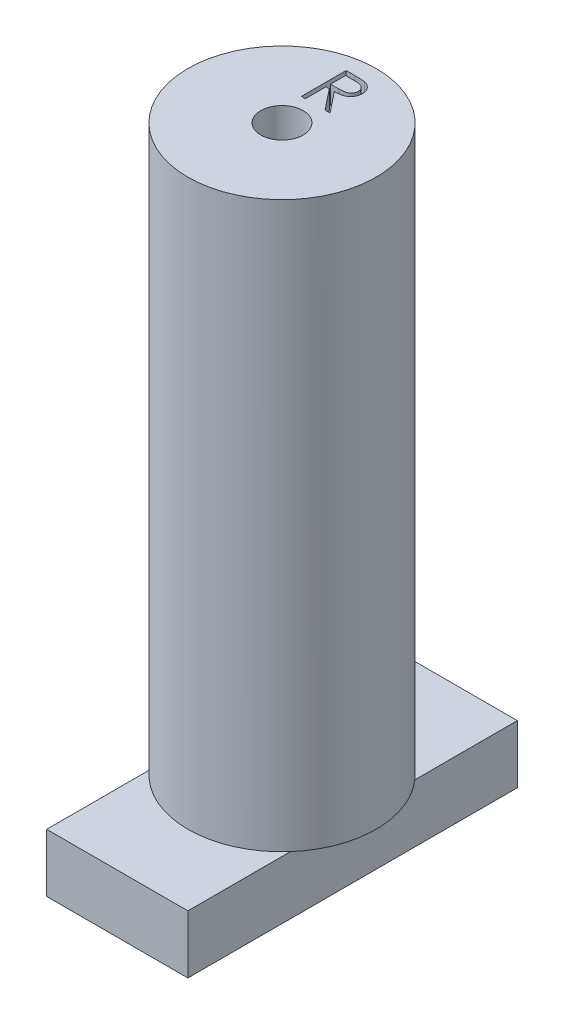
SolidWorks part; units mm, degrees
ref_plane "Front Plane" through (0, 0, 0) normal (0, 0, 1) x (1, 0, 0)
ref_plane "Top Plane" through (0, 0, 0) normal (0, 1, 0) x (1, 0, 0)
ref_plane "Right Plane" through (0, 0, 0) normal (1, 0, 0) x (0, 0, -1)
sketch "Sketch1" plane through (0, 0, 0) normal (0, 1, 0) x (1, 0, 0)
  circle A0 centre (0, 0) radius 10
  dimension "D1" = 20
extrude "Boss-Extrude1" add sketch "Sketch1" along normal blind 4
sketch "Sketch2" plane through (0, 4, 0) normal (0, 1, 0) x (1, 0, 0)
  circle A1 centre (0, 0) radius 3.5
  circle A2 centre (0, 0) radius 8
  circle A3 centre (0, 0) radius 8
  circle A4 centre (0, 0) radius 10 construction
  circle A5 centre (0, 0) radius 10
  circle M2 centre (0, 0) radius 10
  dimension "D2" = 7
  dimension "D1" = 2
extrude "Boss-Extrude2" add sketch "Sketch2" along normal blind 52 contours A1 | A3 M2
sketch "Sketch3" plane through (0, 56, 0) normal (0, 1, 0) x (1, 0, 0)
  circle A0 centre (0, 0) radius 10 construction
  circle A1 centre (0, 0) radius 10
extrude "Boss-Extrude3" add sketch "Sketch3" along normal blind 4
sketch "Sketch4" plane through (0, 60, 0) normal (0, 1, 0) x (1, 0, 0)
  line L0 (-9.3832, 3.4577) -> (9.3832, 3.4577) construction
  circle A0 centre (0, 0) radius 10 construction
  text T0 "R" font "Century Gothic" height in points 18
extrude "Cut-Extrude1" cut sketch "Sketch4" against normal blind 2
sketch "Sketch5" plane through (0, 60, 0) normal (0, 1, 0) x (1, 0, 0)
  circle A0 centre (0, 0) radius 2.25
  dimension "D1" = 4.5
extrude "Cut-Extrude2" cut sketch "Sketch5" against normal blind 50
sketch "Sketch6" plane through (0, 0, 0) normal (0, -1, 0) x (1, 0, 0)
  line L0 (0, 10) -> (0, -10) construction
  line L1 (-10, 0) -> (10, 0) construction
  line L2 (0, 17.5) -> (0, -17.5) construction
  line L3 (-7.5, 17.5) -> (7.5, 17.5)
  line L4 (-7.5, 17.5) -> (-7.5, -17.5)
  line L5 (-7.5, -17.5) -> (7.5, -17.5)
  line L6 (7.5, 17.5) -> (7.5, -17.5)
  line L7 (-7.5, 0) -> (7.5, 0) construction
  circle A0 centre (0, 0) radius 10 construction
  dimension "D1" = 35
  dimension "D2" = 15
extrude "Boss-Extrude4" add sketch "Sketch6" along normal blind 6.18
sketch "Sketch7" plane through (0, -6.18, 0) normal (0, -1, 0) x (1, 0, 0)
  line L0 (0, 17.5) -> (0, -17.5) construction
  line L1 (7.5, 17.5) -> (-7.5, 17.5) construction
  line L2 (-7.5, -17.5) -> (7.5, -17.5) construction
  line L3 (-7.5, 0) -> (7.5, 0) construction
  line L4 (-7.5, 17.5) -> (-7.5, -17.5) construction
  line L5 (7.5, -6.6144) -> (7.5, 6.6144) construction
  line L6 (0, 6.5) -> (0, -6.5) construction
  line L7 (-1.59, 6.5) -> (1.59, 6.5)
  line L8 (-1.59, 6.5) -> (-1.59, -6.5)
  line L9 (-1.59, -6.5) -> (1.59, -6.5)
  line L10 (1.59, 6.5) -> (1.59, -6.5)
  line L11 (-1.59, 0) -> (1.59, 0) construction
  dimension "D1" = 3.18
  dimension "D2" = 13
extrude "Cut-Extrude3" cut sketch "Sketch7" against normal blind 4.18
